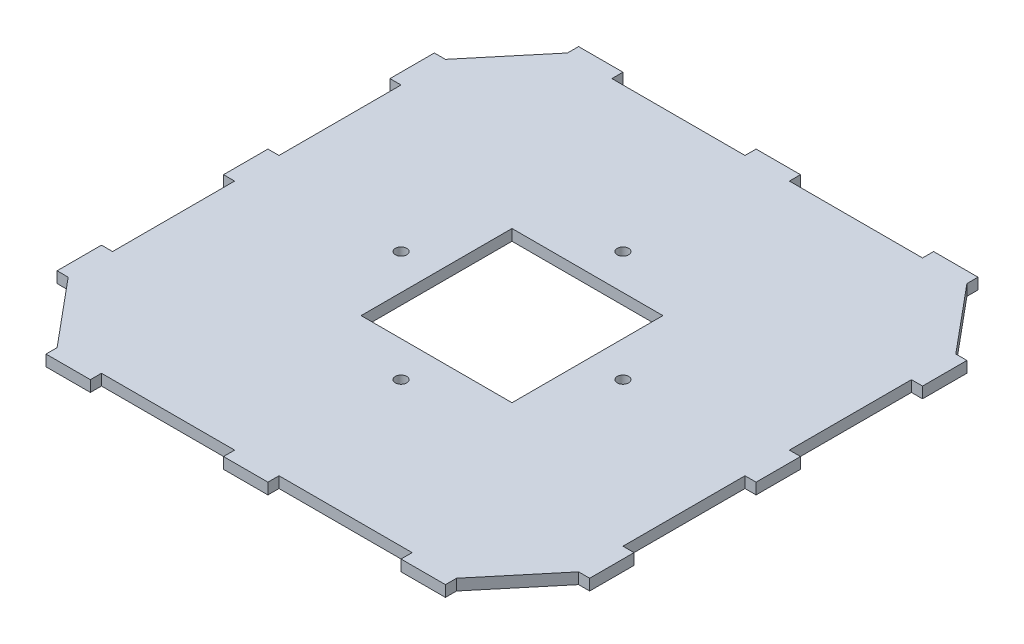
SolidWorks part; units mm, degrees
ref_plane "Front Plane" through (0, 0, 0) normal (0, 0, 1) x (1, 0, 0)
ref_plane "Top Plane" through (0, 0, 0) normal (0, 1, 0) x (1, 0, 0)
ref_plane "Right Plane" through (0, 0, 0) normal (1, 0, 0) x (0, 0, -1)
sketch "Sketch1" plane through (0, 0, 0) normal (0, 1, 0) x (1, 0, 0)
  line L43 (-154.2532, 91.5036) -> (137.8468, 91.5036)
  line L44 (-154.2532, 91.5036) -> (-154.2532, -200.5964)
  line L45 (-154.2532, -200.5964) -> (137.8468, -200.5964)
  line L46 (137.8468, 91.5036) -> (137.8468, -200.5964)
  dimension "D1" = 292.1
  dimension "D2" = 292.1
extrude "Boss-Extrude1" add sketch "Sketch1" along normal blind 6.35
sketch "Sketch3" plane through (-154.2532, 0, 0) normal (-1, 0, 0) x (0, 0, 1)
  line L0 (-91.5036, 6.35) -> (200.5964, 6.35) construction
  line L1 (-53.4036, 6.35) -> (-28.0036, 6.35)
  line L2 (-53.4036, 6.35) -> (-53.4036, 0)
  line L3 (-53.4036, 0) -> (-28.0036, 0)
  line L4 (-28.0036, 6.35) -> (-28.0036, 0)
  line L5 (137.0964, 6.35) -> (162.4964, 6.35)
  line L6 (137.0964, 6.35) -> (137.0964, 0)
  line L7 (137.0964, 0) -> (162.4964, 0)
  line L8 (162.4964, 6.35) -> (162.4964, 0)
  line L9 (-91.5036, 0) -> (200.5964, 0) construction
  line L10 (-91.5036, 6.35) -> (-91.5036, 0) construction
  line L11 (200.5964, 6.35) -> (200.5964, 0) construction
  line L12 (41.8464, 6.35) -> (67.2464, 6.35)
  line L13 (41.8464, 6.35) -> (41.8464, 0)
  line L14 (41.8464, 0) -> (67.2464, 0)
  line L15 (67.2464, 6.35) -> (67.2464, 0)
  dimension "D1" = 25.4
  dimension "D2" = 6.35
  dimension "D3" = 6.35
  dimension "D4" = 38.1
  dimension "D5" = 38.1
  dimension "D6" = 25.4
  dimension "D7" = 6.35
  dimension "D8" = 133.35
extrude "Boss-Extrude2" add sketch "Sketch3" along normal blind 6.35
ref_plane "Plane1" through (-8.2032, 0, 0) normal (-1, 0, 0) x (0, 0, 1)
mirror "Mirror1" about plane through (-8.2032, 0, 0) normal (-1, 0, 0) of "Boss-Extrude2"
sketch "Sketch4" plane through (0, 0, -91.5036) normal (0, 0, -1) x (-1, 0, 0)
  line L0 (-137.8468, 6.35) -> (154.2532, 6.35) construction
  line L1 (-106.0968, 6.35) -> (-80.6968, 6.35)
  line L2 (-106.0968, 6.35) -> (-106.0968, 0)
  line L3 (-106.0968, 0) -> (-80.6968, 0)
  line L4 (-80.6968, 6.35) -> (-80.6968, 0)
  line L5 (97.1032, 6.35) -> (122.5032, 6.35)
  line L6 (97.1032, 6.35) -> (97.1032, 0)
  line L7 (97.1032, 0) -> (122.5032, 0)
  line L8 (122.5032, 6.35) -> (122.5032, 0)
  line L9 (-137.8468, 0) -> (154.2532, 0) construction
  line L10 (-137.8468, 6.35) -> (-137.8468, 0) construction
  line L11 (154.2532, 6.35) -> (154.2532, 0) construction
  line L12 (-4.4968, 6.35) -> (20.9032, 6.35)
  line L13 (-4.4968, 6.35) -> (-4.4968, 0)
  line L14 (-4.4968, 0) -> (20.9032, 0)
  line L15 (20.9032, 6.35) -> (20.9032, 0)
  dimension "D1" = 6.35
  dimension "D2" = 6.35
  dimension "D3" = 25.4
  dimension "D4" = 31.75
  dimension "D5" = 31.75
  dimension "D6" = 25.4
  dimension "D7" = 6.35
  dimension "D8" = 133.35
extrude "Boss-Extrude3" add sketch "Sketch4" along normal blind 6.35
ref_plane "Plane3" through (0, 0, 54.5464) normal (0, 0, 1) x (1, 0, 0)
mirror "Mirror2" about plane through (0, 0, 54.5464) normal (0, 0, 1) of "Boss-Extrude3"
sketch "Sketch5" plane through (0, 0, 0) normal (0, -1, 0) x (1, 0, 0)
  line L0 (137.8468, 200.5964) -> (137.8468, 162.4964) construction
  line L1 (106.0968, 200.5964) -> (137.8468, 200.5964) construction
  line L2 (137.8468, 137.0964) -> (137.8468, 67.2464) construction
  line L3 (-51.3832, 11.3664) -> (34.9768, 11.3664)
  line L4 (-51.3832, 11.3664) -> (-51.3832, 97.7264)
  line L5 (-51.3832, 97.7264) -> (34.9768, 97.7264)
  line L6 (34.9768, 11.3664) -> (34.9768, 97.7264)
  line L7 (106.0968, 200.5964) -> (137.8468, 162.4964)
  line L8 (80.6968, -91.5036) -> (4.4968, -91.5036) construction
  line L9 (137.8468, 162.4964) -> (137.8468, 200.5964)
  line L10 (137.8468, 200.5964) -> (106.0968, 200.5964)
  line L11 (-122.5032, 200.5964) -> (-154.2532, 200.5964)
  line L12 (-154.2532, 200.5964) -> (-154.2532, 162.4964)
  line L13 (-154.2532, 162.4964) -> (-122.5032, 200.5964)
  line L14 (-154.2532, -53.4036) -> (-154.2532, -91.5036)
  line L15 (-154.2532, -91.5036) -> (-122.5032, -91.5036)
  line L16 (-122.5032, -91.5036) -> (-154.2532, -53.4036)
  line L17 (106.0968, -91.5036) -> (137.8468, -91.5036)
  line L18 (137.8468, -91.5036) -> (137.8468, -53.4036)
  line L19 (137.8468, -53.4036) -> (106.0968, -91.5036)
  circle A0 centre (-8.2032, 118.0464) radius 3.25
  circle A1 centre (55.2968, 54.5464) radius 3.25
  circle A2 centre (-8.2032, -8.9536) radius 3.25
  circle A3 centre (-71.7032, 54.5464) radius 3.25
  dimension "D1" = 86.36
  dimension "D8" = 63.5
  dimension "D9" = 63.5
  dimension "D10" = 63.5
  dimension "D11" = 6.5
  dimension "D2" = 86.36
  dimension "D3" = 102.87
  dimension "D4" = 102.87
  dimension "D5" = 146.05
  dimension "D6" = 146.05
  dimension "D7" = 63.5
extrude "Cut-Extrude1" cut sketch "Sketch5" against normal blind 6.35
